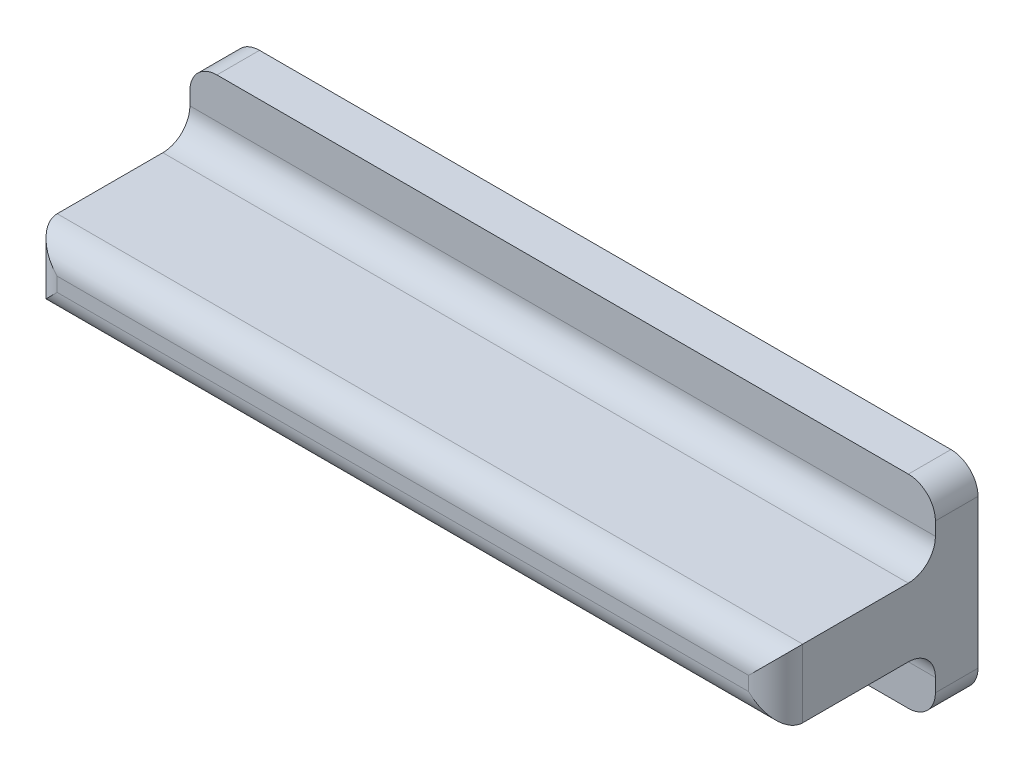
SolidWorks part; units mm, degrees
material "ABS"
ref_plane "X-Y Datum" through (0, 0, 0) normal (0, 0, 1) x (1, 0, 0)
ref_plane "X-Z Datum" through (0, 0, 0) normal (0, 1, 0) x (1, 0, 0)
ref_plane "Y-Z Datum" through (0, 0, 0) normal (1, 0, 0) x (0, 0, -1)
sketch "Sketch1" plane through (0, 0, 0) normal (0, 0, 1) x (1, 0, 0)
  line L1 (-35, -9.525) -> (35, -9.525)
  line L2 (-35, -9.525) -> (-35, 9.525)
  line L3 (-35, 9.525) -> (35, 9.525)
  line L4 (35, -9.525) -> (35, 9.525)
  line L5 (-35, -9.525) -> (35, 9.525) construction
  line L6 (-35, 9.525) -> (35, -9.525) construction
  point P0 (0, 0)
  dimension "D1" = 19.05
  dimension "D2" = 70
extrude "Boss-Extrude1" add sketch "Sketch1" along normal blind 4
sketch "Sketch2" plane through (0, 0, 4) normal (0, 0, 1) x (1, 0, 0)
  line L0 (35, -9.525) -> (35, 9.525) construction
  line L1 (-35, -3.1994) -> (35, -3.1994)
  line L2 (-35, -3.1994) -> (-35, 3.1994)
  line L3 (-35, 3.1994) -> (35, 3.1994)
  line L4 (35, -3.1994) -> (35, 3.1994)
  line L5 (-35, -3.1994) -> (35, 3.1994) construction
  line L6 (-35, 3.1994) -> (35, -3.1994) construction
  point P0 (0, 0)
  dimension "D1" = 6.3987
extrude "Boss-Extrude2" add sketch "Sketch2" along normal blind 15
fillet "Fillet1" radius 2.54 10 edges at (-35, -9.525, 2) (-35, 9.525, 2) (35, 9.525, 2) (35, -9.525, 2) (0, -3.1994, 19) (-35, 0, 19) (0, 3.1994, 19) (35, 0, 19) (0, 3.1994, 4) (0, -3.1994, 4)
